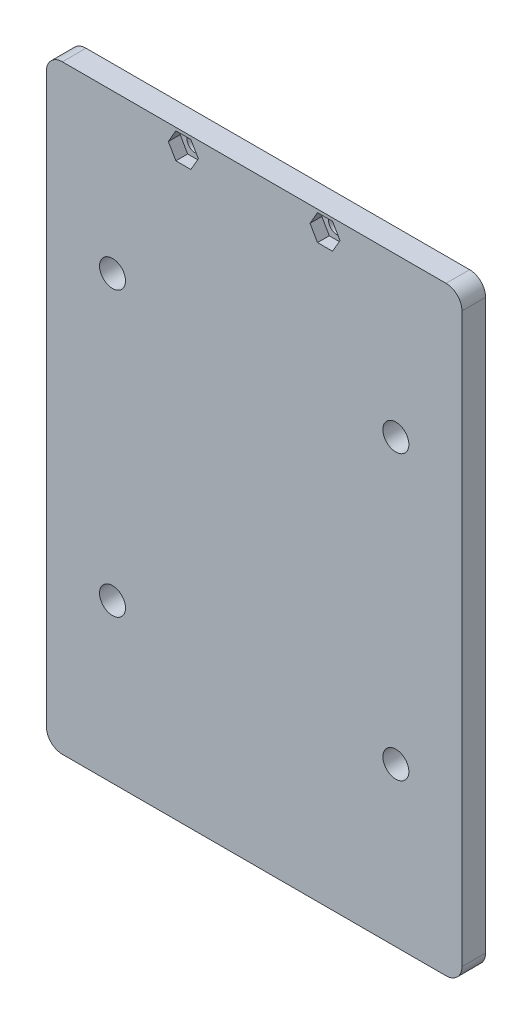
SolidWorks part; units mm, degrees
ref_plane "Plan de face" through (0, 0, 0) normal (0, 0, 1) x (1, 0, 0)
ref_plane "Plan de dessus" through (0, 0, 0) normal (0, 1, 0) x (1, 0, 0)
ref_plane "Plan de droite" through (0, 0, 0) normal (1, 0, 0) x (0, 0, -1)
sketch "Sketch1" plane through (0, 0, 0) normal (0, 0, 1) x (1, 0, 0)
  line L8 (445.8814, -1323.7452) -> (445.8814, -1203.5052)
  line L9 (442.5014, -1200.1252) -> (361.2614, -1200.1252)
  line L10 (357.8814, -1203.5052) -> (357.8814, -1323.7452)
  line L11 (361.2614, -1327.1252) -> (442.5014, -1327.1252)
  circle A0 centre (371.8814, -1233.6252) radius 2.75
  circle A1 centre (431.8814, -1233.6252) radius 2.75
  circle A2 centre (371.8814, -1293.6252) radius 2.75
  circle A3 centre (431.8814, -1293.6252) radius 2.75
  arc A8 (442.5014, -1327.1252) -> (445.8814, -1323.7452) centre (442.5014, -1323.7452) ccw
  arc A9 (445.8814, -1203.5052) -> (442.5014, -1200.1252) centre (442.5014, -1203.5052) ccw
  arc A10 (361.2614, -1200.1252) -> (357.8814, -1203.5052) centre (361.2614, -1203.5052) ccw
  arc A11 (357.8814, -1323.7452) -> (361.2614, -1327.1252) centre (361.2614, -1323.7452) ccw
  circle A12 centre (386.8814, -1203.5152) radius 1.75
  circle A14 centre (416.8814, -1203.5152) radius 1.75
  dimension "D2" = 5.5
  dimension "D3" = 5.5
  dimension "D4" = 5.5
  dimension "D5" = 5.5
  dimension "D6" = 3.5
  dimension "D7" = 3.5
extrude "Boss-Extrude1" add sketch "Sketch1" along normal blind 5
sketch "Sketch2" plane through (0, 0, 5) normal (0, 0, 1) x (1, 0, 0)
  line L0 (442.5014, -1200.1252) -> (361.2614, -1200.1252) construction
  line L1 (388.4692, -1200.7652) -> (385.2937, -1200.7652)
  line L2 (385.2937, -1200.7652) -> (383.706, -1203.5152)
  line L3 (383.706, -1203.5152) -> (385.2937, -1206.2652)
  line L4 (385.2937, -1206.2652) -> (388.4692, -1206.2652)
  line L5 (388.4692, -1206.2652) -> (390.0569, -1203.5152)
  line L6 (390.0569, -1203.5152) -> (388.4692, -1200.7652)
  line L7 (418.4692, -1200.7652) -> (415.2937, -1200.7652)
  line L8 (415.2937, -1200.7652) -> (413.706, -1203.5152)
  line L9 (413.706, -1203.5152) -> (415.2937, -1206.2652)
  line L10 (415.2937, -1206.2652) -> (418.4692, -1206.2652)
  line L11 (418.4692, -1206.2652) -> (420.0569, -1203.5152)
  line L12 (420.0569, -1203.5152) -> (418.4692, -1200.7652)
  circle A0 centre (386.8814, -1203.5152) radius 2.75 construction
  circle A1 centre (416.8814, -1203.5152) radius 2.75 construction
  dimension "D1" = 5.5
  dimension "D2" = 5.5
extrude "Cut-Extrude1" cut sketch "Sketch2" against normal blind 2.5
